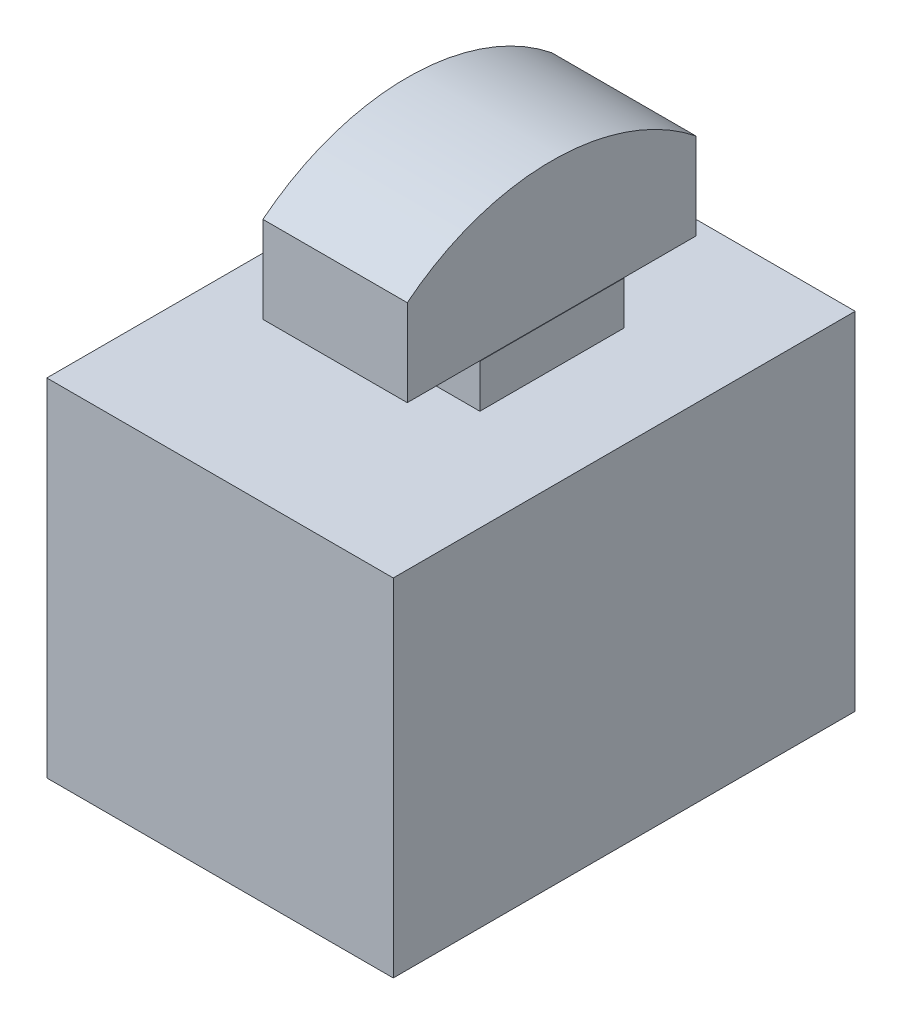
SolidWorks part; units mm, degrees
material "POM 아세탈 공중합체"
ref_plane "정면" through (0, 0, 0) normal (0, 0, 1) x (1, 0, 0)
ref_plane "윗면" through (0, 0, 0) normal (0, 1, 0) x (1, 0, 0)
ref_plane "우측면" through (0, 0, 0) normal (1, 0, 0) x (0, 0, -1)
sketch "스케치1" plane through (0, 0, 0) normal (0, 0, 1) x (1, 0, 0)
  line L1 (-6, 6) -> (6, 6)
  line L2 (-6, 6) -> (-6, -6)
  line L3 (-6, -6) -> (6, -6)
  line L4 (6, 6) -> (6, -6)
  line L5 (-6, 6) -> (6, -6) construction
  line L6 (-6, -6) -> (6, 6) construction
  point P0 (0, 0)
  dimension "D1" = 12
  dimension "D2" = 12
extrude "보스-돌출1" add sketch "스케치1" along normal blind 16
sketch "스케치2" plane through (0, 6, 0) normal (0, 1, 0) x (1, 0, 0)
  line L0 (6, 0) -> (-6, 0) construction
  line L1 (-2.5, -4.5) -> (2.5, -4.5)
  line L2 (-2.5, -4.5) -> (-2.5, -9.5)
  line L3 (-2.5, -9.5) -> (2.5, -9.5)
  line L4 (2.5, -4.5) -> (2.5, -9.5)
  line L5 (-2.5, -4.5) -> (2.5, -9.5) construction
  line L6 (-2.5, -9.5) -> (2.5, -4.5) construction
  line L7 (-6, -16) -> (-6, 0) construction
  point P0 (0, -7)
  dimension "D1" = 7
  dimension "D2" = 5
  dimension "D3" = 5
  dimension "D4" = 6
extrude "보스-돌출2" add sketch "스케치2" along normal blind 1.5
sketch "스케치3" plane through (0, 7.5, 0) normal (0, 1, 0) x (1, 0, 0)
  line L0 (6, 0) -> (-6, 0) construction
  line L1 (-2.515, -2) -> (2.485, -2)
  line L2 (-2.515, -2) -> (-2.515, -12)
  line L3 (-2.515, -12) -> (2.485, -12)
  line L4 (2.485, -2) -> (2.485, -12)
  line L5 (-2.515, -2) -> (2.485, -12) construction
  line L6 (-2.515, -12) -> (2.485, -2) construction
  point P0 (-0.015, -7)
  dimension "D1" = 2
  dimension "D2" = 5
  dimension "D3" = 2.5
extrude "보스-돌출3" add sketch "스케치3" along normal blind 3
sketch "스케치4" plane through (-2.515, 0, 0) normal (-1, 0, 0) x (0, 0, 1)
  line L0 (2, 10.5) -> (12, 10.5)
  arc A0 (2, 10.5) -> (12, 10.5) centre (7, 4.255) cw
  dimension "D1" = 8
extrude "보스-돌출4" add sketch "스케치4" against normal up to surface (5 mm away) up to face at (2.485, 8.5, 7)
